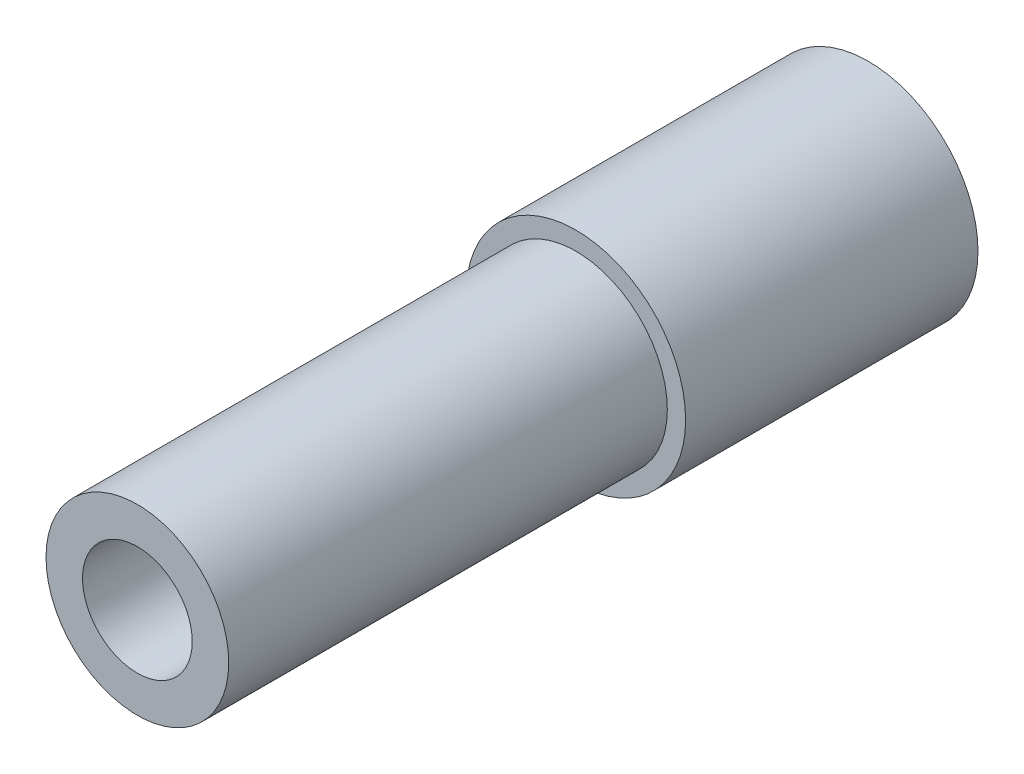
SolidWorks part; units mm, degrees
material "1060-H12 Rod (SS)"
ref_plane "Front Plane" through (0, 0, 0) normal (0, 0, 1) x (1, 0, 0)
ref_plane "Top Plane" through (0, 0, 0) normal (0, 1, 0) x (1, 0, 0)
ref_plane "Right Plane" through (0, 0, 0) normal (1, 0, 0) x (0, 0, -1)
sketch "Sketch1" plane through (0, 0, 0) normal (0, 0, 1) x (1, 0, 0)
  circle A0 centre (0, 0) radius 11
  circle A1 centre (0, 0) radius 15
  dimension "D1" = 22
  dimension "D2" = 30
extrude "Boss-Extrude1" add sketch "Sketch1" along normal blind 40
sketch "Sketch2" plane through (0, 0, 40) normal (0, 0, 1) x (1, 0, 0)
  circle A0 centre (0, 0) radius 12.5
  circle A1 centre (0, 0) radius 7.5
  dimension "D1" = 25
  dimension "D2" = 15
extrude "Boss-Extrude2" add sketch "Sketch2" along normal blind 60
